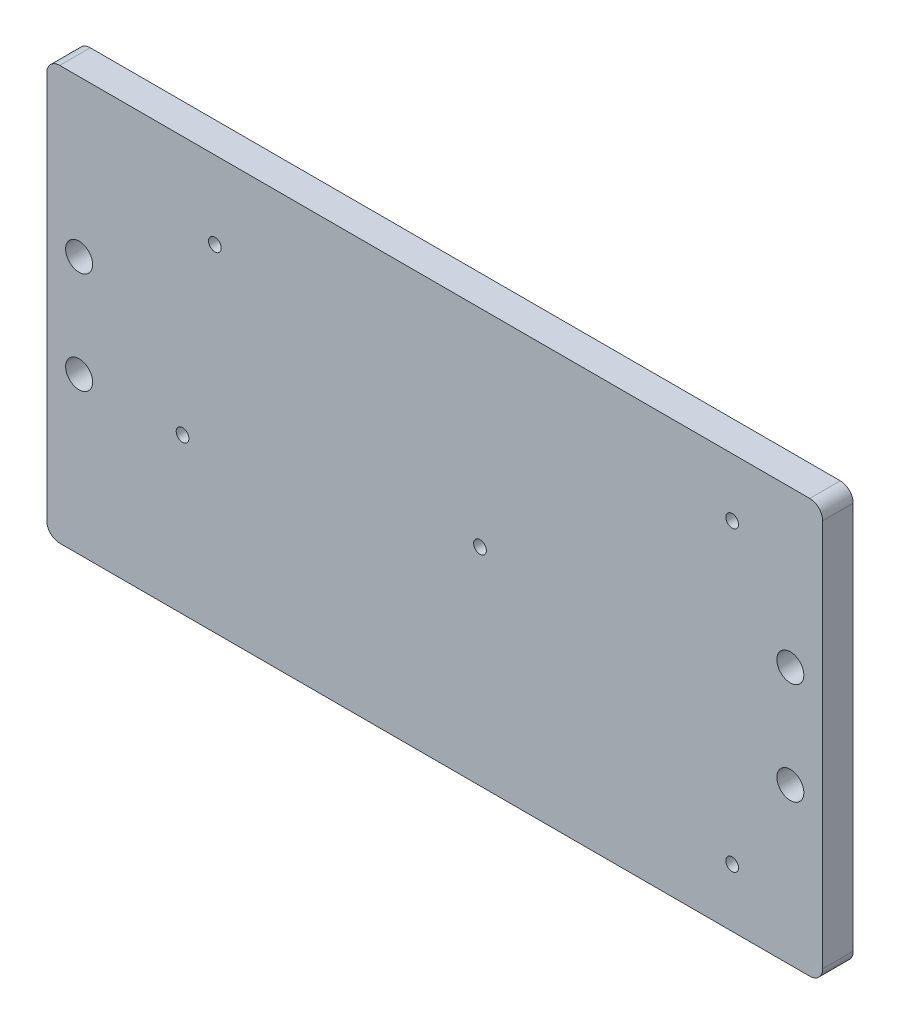
SolidWorks part; units mm, degrees
ref_plane "Front Plane" through (0, 0, 0) normal (0, 0, 1) x (1, 0, 0)
ref_plane "Top Plane" through (0, 0, 0) normal (0, 1, 0) x (1, 0, 0)
ref_plane "Right Plane" through (0, 0, 0) normal (1, 0, 0) x (0, 0, -1)
other "Configuration Table"
ref_plane "Plane1" through (0, 0, -12) normal (0, 0, -1) x (-1, 0, 0)
sketch "Sketch1" plane through (0, 0, -12) normal (0, 0, -1) x (-1, 0, 0)
  line L0 (-527.9771, 394.1064) -> (-375.5771, 394.1064) construction
  line L1 (-525.4371, 434.7464) -> (-378.1171, 434.7464)
  line L2 (-527.9771, 432.2064) -> (-527.9771, 356.0064)
  line L3 (-525.4371, 353.4664) -> (-378.1171, 353.4664)
  line L4 (-399.7071, 428.3964) -> (-512.7371, 428.3964)
  line L5 (-515.2771, 425.8564) -> (-515.2771, 362.3564)
  line L6 (-512.7371, 359.8164) -> (-399.7071, 359.8164)
  line L7 (-397.1671, 362.3564) -> (-397.1671, 425.8564)
  line L16 (-399.7071, 428.3964) -> (-512.7371, 428.3964) construction
  line L17 (-515.2771, 425.8564) -> (-515.2771, 362.3564) construction
  line L18 (-512.7371, 359.8164) -> (-399.7071, 359.8164) construction
  line L19 (-397.1671, 362.3564) -> (-397.1671, 425.8564) construction
  line L20 (-375.5771, 432.2064) -> (-375.5771, 356.0064)
  line L21 (-527.9771, 404.1064) -> (-375.5771, 404.1064) construction
  line L22 (-375.5771, 384.1064) -> (-527.9771, 384.1064) construction
  line L23 (-451.7771, 404.1064) -> (-451.7771, 394.1064) construction
  line L24 (-451.7771, 394.1064) -> (-451.7771, 384.1064) construction
  line L25 (-527.9771, 404.1064) -> (-521.6271, 404.1064) construction
  line L26 (-521.6271, 404.1064) -> (-515.2771, 404.1064) construction
  circle A0 centre (-510.1971, 364.8964) radius 1.575 construction
  circle A1 centre (-402.2471, 383.9464) radius 1.575 construction
  circle A2 centre (-408.5971, 419.5064) radius 1.575 construction
  circle A3 centre (-460.6671, 394.1064) radius 1.575 construction
  arc A4 (-397.1671, 425.8564) -> (-399.7071, 428.3964) centre (-399.7071, 425.8564) ccw
  arc A5 (-512.7371, 428.3964) -> (-515.2771, 425.8564) centre (-512.7371, 425.8564) ccw
  arc A6 (-515.2771, 362.3564) -> (-512.7371, 359.8164) centre (-512.7371, 362.3564) ccw
  arc A7 (-399.7071, 359.8164) -> (-397.1671, 362.3564) centre (-399.7071, 362.3564) ccw
  arc A16 (-397.1671, 425.8564) -> (-399.7071, 428.3964) centre (-399.7071, 425.8564) ccw construction
  arc A17 (-512.7371, 428.3964) -> (-515.2771, 425.8564) centre (-512.7371, 425.8564) ccw construction
  arc A18 (-515.2771, 362.3564) -> (-512.7371, 359.8164) centre (-512.7371, 362.3564) ccw construction
  arc A19 (-399.7071, 359.8164) -> (-397.1671, 362.3564) centre (-399.7071, 362.3564) ccw construction
  circle A20 centre (-510.1971, 423.3164) radius 1.575 construction
  circle A21 centre (-510.1971, 364.8964) radius 1.575 construction
  circle A22 centre (-402.2471, 383.9464) radius 1.575 construction
  circle A23 centre (-408.5971, 419.5064) radius 1.575 construction
  circle A24 centre (-460.6671, 394.1064) radius 1.575 construction
  circle A25 centre (-510.1971, 423.3164) radius 1.575 construction
  circle A26 centre (-521.6271, 404.1064) radius 6 construction
  circle A27 centre (-521.6271, 384.1064) radius 6 construction
  circle A28 centre (-381.9271, 384.1064) radius 6 construction
  circle A29 centre (-381.9271, 404.1064) radius 6 construction
  arc A30 (-378.1171, 434.7464) -> (-375.5771, 432.2064) centre (-378.1171, 432.2064) cw
  arc A31 (-378.1171, 353.4664) -> (-375.5771, 356.0064) centre (-378.1171, 356.0064) ccw
  arc A32 (-527.9771, 356.0064) -> (-525.4371, 353.4664) centre (-525.4371, 356.0064) ccw
  arc A33 (-525.4371, 434.7464) -> (-527.9771, 432.2064) centre (-525.4371, 432.2064) ccw
  point P33 (-515.2771, 394.1064)
  dimension "D3" = 12
  dimension "D4" = 69.85
  dimension "D8" = 2.54
  dimension "D2" = 20
  dimension "D5" = 69.85
  dimension "D6" = 12.7
  dimension "D7" = 6.35
  dimension "D1" = 0
extrude "Boss-Extrude1" add sketch "Sketch1" along normal blind 6
hole_wizard "M5 Clearance Hole1" positions "Sketch3" profile "Sketch4" hole size "M5" standard "ANSI Metric" end condition through all
sketch "Sketch3" plane through (0, 0, -18) normal (0, 0, -1) x (-1, 0, 0)
  point P0 (-521.6271, 404.1064)
  point P3 (-521.6271, 384.1064)
  point P6 (-381.9271, 384.1064)
  point P9 (-381.9271, 404.1064)
sketch "Sketch4" plane through (521.6271, 404.1064, -18) normal (1, 0, 0) x (0, 1, 0)
  line L0 (0, 0) -> (0, 6)
  line L1 (0, 6) -> (2.65, 6)
  line L2 (2.65, 6) -> (2.65, 0)
  line L5 (2.65, 0) -> (0, 0)
  line L11 (0, -6.35) -> (0, 107.95) construction
  dimension "Thru Hole Dia." = 5.3
  dimension "Thru Hole Depth" = 6
hole_wizard "M3x0.5 Tapped Hole1" positions "Sketch5" profile "Sketch6" tap size "M3x0.5" standard "ANSI Metric" end condition through all
sketch "Sketch5" plane through (0, 0, -18) normal (0, 0, -1) x (-1, 0, 0)
  point P0 (-510.1971, 423.3164)
  point P3 (-408.5971, 419.5064)
  point P6 (-460.6671, 394.1064)
  point P9 (-402.2471, 383.9464)
  point P12 (-510.1971, 364.8964)
sketch "Sketch6" plane through (510.1971, 423.3164, -18) normal (1, 0, 0) x (0, 1, 0)
  line L0 (0, 0) -> (0, 6)
  line L1 (0, 6) -> (1.25, 6)
  line L2 (1.25, 6) -> (1.25, 0)
  line L5 (1.25, 0) -> (0, 0)
  line L11 (0, -6.35) -> (0, 107.95) construction
  dimension "Thru Tap Drill Dia." = 2.5
  dimension "Thru Tap Drill Depth" = 6
cosmetic thread "Hole Thread1" parameters "D2"=3
cosmetic thread "Hole Thread2" parameters "D2"=3
cosmetic thread "Hole Thread3" parameters "D2"=3
cosmetic thread "Hole Thread4" parameters "D2"=3
cosmetic thread "Hole Thread5" parameters "D2"=3
